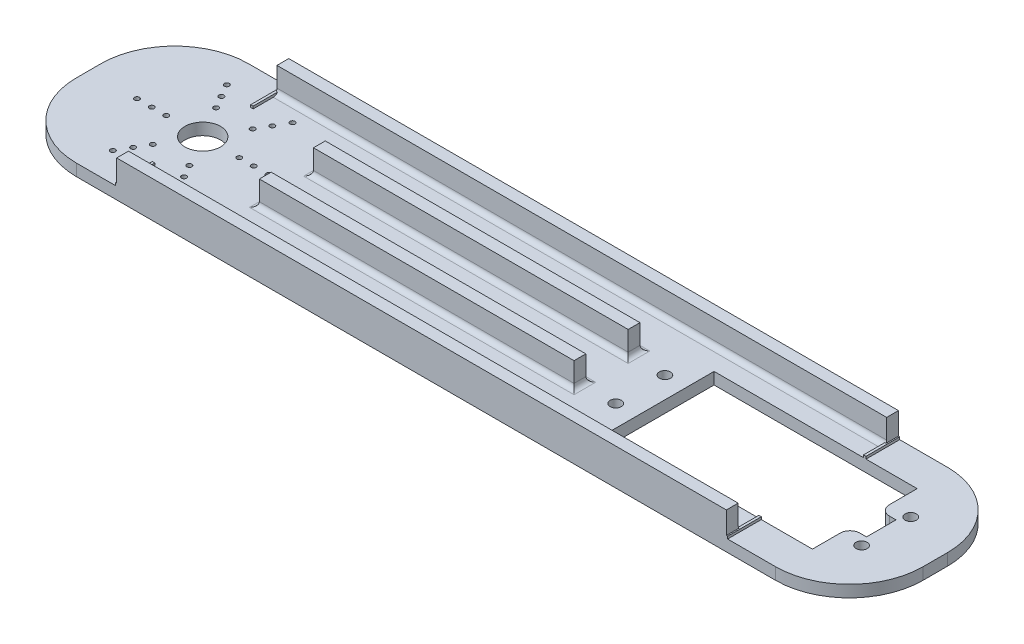
SolidWorks part; units mm, degrees
ref_plane "Front Plane" through (0, 0, 0) normal (0, 0, 1) x (1, 0, 0)
ref_plane "Top Plane" through (0, 0, 0) normal (0, 1, 0) x (1, 0, 0)
ref_plane "Right Plane" through (0, 0, 0) normal (1, 0, 0) x (0, 0, -1)
sketch "Sketch1" plane through (0, 0, 0) normal (0, 1, 0) x (1, 0, 0)
  line L1 (-44.6771, 38.9958) -> (127.5229, 38.9958)
  line L2 (-44.6771, 38.9958) -> (-44.6771, 3.9958)
  line L3 (-44.6771, 3.9958) -> (127.5229, 3.9958)
  line L4 (127.5229, 38.9958) -> (127.5229, 3.9958)
  dimension "D1" = 172.2
  dimension "D2" = 35
extrude "Boss-Extrude1" add sketch "Sketch1" along normal blind 2.4
sketch "Sketch2" plane through (0, 2.4, 0) normal (0, 1, 0) x (1, 0, 0)
  line L0 (-21.4771, 38.9958) -> (-21.4771, 2.4158) construction
  line L1 (127.5229, 38.9958) -> (-44.6771, 38.9958) construction
  line L2 (-44.6771, 21.4958) -> (127.5229, 21.4958) construction
  line L3 (-44.6771, 38.9958) -> (-44.6771, 3.9958) construction
  line L4 (127.5229, 3.9958) -> (127.5229, 38.9958) construction
  line L5 (112.5229, 38.9958) -> (112.5229, 3.9958) construction
  line L6 (-44.6771, 3.9958) -> (127.5229, 3.9958) construction
  line L7 (72.5229, 38.9958) -> (72.5229, 3.9958) construction
  line L9 (72.5229, 31.4958) -> (112.5229, 31.4958)
  line L10 (72.5229, 31.4958) -> (72.5229, 11.4958)
  line L11 (72.5229, 11.4958) -> (112.5229, 11.4958)
  line L12 (112.5229, 31.4958) -> (112.5229, 11.4958)
  circle A0 centre (67.5229, 26.4958) radius 1.13
  circle A1 centre (117.5229, 26.4958) radius 1.13
  circle A2 centre (117.5229, 16.4958) radius 1.13
  circle A3 centre (67.5229, 16.4958) radius 1.13
  circle A4 centre (-21.4771, 21.4958) radius 3.625
  circle A5 centre (-28.9071, 21.4958) radius 0.5
  circle A6 centre (-31.8421, 21.4958) radius 0.5
  circle A7 centre (-34.8471, 21.4958) radius 0.5
  circle A8 centre (-25.1921, 27.9303) radius 0.5
  circle A9 centre (-28.1621, 33.0745) radius 0.5
  circle A10 centre (-26.6596, 30.4721) radius 0.5
  circle A11 centre (-17.7621, 27.9303) radius 0.5
  circle A12 centre (-14.7921, 33.0745) radius 0.5
  circle A13 centre (-16.2946, 30.4721) radius 0.5
  circle A14 centre (-14.0471, 21.4958) radius 0.5
  circle A15 centre (-8.1071, 21.4958) radius 0.5
  circle A16 centre (-11.1121, 21.4958) radius 0.5
  circle A17 centre (-17.7621, 15.0612) radius 0.5
  circle A18 centre (-14.7921, 9.917) radius 0.5
  circle A19 centre (-16.2946, 12.5194) radius 0.5
  circle A20 centre (-25.1921, 15.0612) radius 0.5
  circle A21 centre (-28.1621, 9.917) radius 0.5
  circle A22 centre (-26.6596, 12.5194) radius 0.5
  point P24 (-21.4771, 21.4958)
  point P37 (-44.6771, 21.4958)
  point P39 (-21.4771, 21.4958)
  point P40 (-21.4771, 21.4958)
  point P72 (-21.4771, 21.4958)
  dimension "D5" = 2.26
  dimension "D6" = 2.26
  dimension "D11" = 7.25
  dimension "D12" = 7.43
  dimension "D13" = 10.365
  dimension "D14" = 13.37
  dimension "D15" = 1
  dimension "D16" = 1
  dimension "D17" = 1
  dimension "D19" = 20
  dimension "D1" = 23.2
  dimension "D2" = 15
  dimension "D3" = 40
  dimension "D4" = 10
  dimension "D7" = 5
  dimension "D8" = 5
  dimension "D9" = 5
  dimension "D10" = 5
  dimension "D18" = 6
extrude "Cut-Extrude1" cut sketch "Sketch2" against normal blind 2.4
sketch "Sketch4" plane through (0, 2.4, 0) normal (0, 1, 0) x (1, 0, 0)
  line L0 (72.5229, 21.4958) -> (127.5229, 21.4958) construction
  line L1 (72.5229, 31.4958) -> (72.5229, 11.4958) construction
  line L2 (127.5229, 3.9958) -> (127.5229, 38.9958) construction
  line L3 (112.5229, 11.4958) -> (112.5229, 31.4958) construction
  line L4 (112.5229, 24.4958) -> (116.5229, 24.4958)
  line L5 (112.5229, 24.4958) -> (112.5229, 18.4958)
  line L6 (112.5229, 18.4958) -> (116.5229, 18.4958)
  line L7 (116.5229, 24.4958) -> (116.5229, 18.4958)
  dimension "D1" = 6
  dimension "D2" = 3
  dimension "D3" = 4
extrude "Cut-Extrude2" cut sketch "Sketch4" against normal blind 2.4
sketch "Sketch5" plane through (0, 2.4, 0) normal (0, 1, 0) x (1, 0, 0)
  line L0 (-21.4771, 21.4958) -> (127.5229, 21.4958) construction
  line L1 (127.5229, 3.9958) -> (127.5229, 38.9958) construction
  line L2 (-21.4771, 38.9958) -> (-21.4771, 3.9958) construction
  line L3 (127.5229, 38.9958) -> (-44.6771, 38.9958) construction
  line L4 (-44.6771, 3.9958) -> (127.5229, 3.9958) construction
  line L5 (102.5229, 38.9958) -> (102.5229, 3.9958) construction
  line L6 (112.5229, 31.4958) -> (72.5229, 31.4958) construction
  line L7 (102.2729, 38.9958) -> (102.7729, 38.9958)
  line L8 (102.2729, 38.9958) -> (102.2729, 31.4958)
  line L9 (102.2729, 31.4958) -> (102.7729, 31.4958)
  line L10 (102.7729, 38.9958) -> (102.7729, 31.4958)
  line L11 (102.7729, 3.9958) -> (102.7729, 11.4958)
  line L12 (102.2729, 11.4958) -> (102.7729, 11.4958)
  line L13 (102.2729, 3.9958) -> (102.2729, 11.4958)
  line L14 (102.2729, 3.9958) -> (102.7729, 3.9958)
  line L15 (-21.2271, 3.9958) -> (-21.2271, 11.4958)
  line L16 (-21.7271, 38.9958) -> (-21.2271, 38.9958)
  line L17 (-21.7271, 38.9958) -> (-21.7271, 31.4958)
  line L18 (-21.7271, 31.4958) -> (-21.2271, 31.4958)
  line L19 (-21.2271, 38.9958) -> (-21.2271, 31.4958)
  line L20 (-21.7271, 11.4958) -> (-21.2271, 11.4958)
  line L21 (-21.7271, 3.9958) -> (-21.7271, 11.4958)
  line L22 (-21.7271, 3.9958) -> (-21.2271, 3.9958)
  dimension "D1" = 124
  dimension "D2" = 0.5
  dimension "D3" = 0.25
  dimension "D4" = 0.25
  dimension "D5" = 0.5
  dimension "D6" = 7.5
extrude "Boss-Extrude2" add sketch "Sketch5" along normal blind 0.5
sketch "Sketch7" plane through (0, 2.4, 0) normal (0, 1, 0) x (1, 0, 0)
  line L0 (71.8729, 32.1458) -> (71.8729, 10.8458)
  line L1 (72.5229, 31.4958) -> (112.5229, 31.4958)
  line L2 (72.5229, 31.4958) -> (72.5229, 11.4958)
  line L3 (72.5229, 11.4958) -> (112.5229, 11.4958)
  line L4 (112.5229, 31.4958) -> (112.5229, 11.4958)
  line L5 (71.8729, 10.8458) -> (113.1729, 10.8458)
  line L6 (113.1729, 32.1458) -> (113.1729, 10.8458)
  line L7 (71.8729, 32.1458) -> (113.1729, 32.1458)
  dimension "D1" = 0.65
extrude "Cut-Extrude3" cut sketch "Sketch7" against normal through all both and the other way through all
sketch "Sketch8" plane through (0, 2.4, 0) normal (0, 1, 0) x (1, 0, 0)
  line L0 (102.5229, 38.9958) -> (102.5229, 3.9958) construction
  line L1 (-21.4771, 38.9958) -> (102.5229, 38.9958)
  line L2 (-21.4771, 38.9958) -> (-21.4771, 36.5958)
  line L3 (-21.4771, 36.5958) -> (102.5229, 36.5958)
  line L4 (102.5229, 38.9958) -> (102.5229, 36.5958)
  line L5 (-3.2566, 3.9958) -> (-3.2566, 38.9958) construction
  line L6 (-21.2271, 3.9958) -> (102.2729, 3.9958) construction
  line L7 (-21.4771, 21.4958) -> (116.5229, 21.4958) construction
  line L8 (-3.2566, 28.1958) -> (60.7434, 28.1958)
  line L9 (-3.2566, 28.1958) -> (-3.2566, 25.7958)
  line L10 (-3.2566, 25.7958) -> (60.7434, 25.7958)
  line L11 (60.7434, 28.1958) -> (60.7434, 25.7958)
  line L12 (116.5229, 18.4958) -> (116.5229, 24.4958) construction
  line L13 (60.7434, 14.7958) -> (60.7434, 17.1958)
  line L14 (-3.2566, 17.1958) -> (60.7434, 17.1958)
  line L15 (-3.2566, 14.7958) -> (-3.2566, 17.1958)
  line L16 (-3.2566, 14.7958) -> (60.7434, 14.7958)
  line L17 (102.5229, 3.9958) -> (102.5229, 6.3958)
  line L18 (-21.4771, 6.3958) -> (102.5229, 6.3958)
  line L19 (-21.4771, 3.9958) -> (-21.4771, 6.3958)
  line L20 (-21.4771, 3.9958) -> (102.5229, 3.9958)
  dimension "D1" = 2.4
  dimension "D2" = 2.4
  dimension "D3" = 64
  dimension "D4" = 8.4
extrude "Boss-Extrude3" add sketch "Sketch8" along normal blind 5
fillet "Fillet1" radius 15 4 edges at (127.5229, 1.2, -3.9958) (127.5229, 1.2, -38.9958) (-44.6771, 1.2, -3.9958) (-44.6771, 1.2, -38.9958)
fillet "Fillet2" radius 2 2 edges at (113.1729, 1.2, -18.4958) (113.1729, 1.2, -24.4958)
fillet "Fillet3" radius 1 10 edges at (40.5229, 2.4, -6.3958) (60.7434, 2.4, -15.9958) (28.7434, 2.4, -17.1958) (60.7434, 2.4, -26.9958) (28.7434, 2.4, -28.1958) (28.7434, 2.4, -14.7958) (-3.2566, 2.4, -15.9958) (-3.2566, 2.4, -26.9958) (28.7434, 2.4, -25.7958) (40.5229, 2.4, -36.5958)
